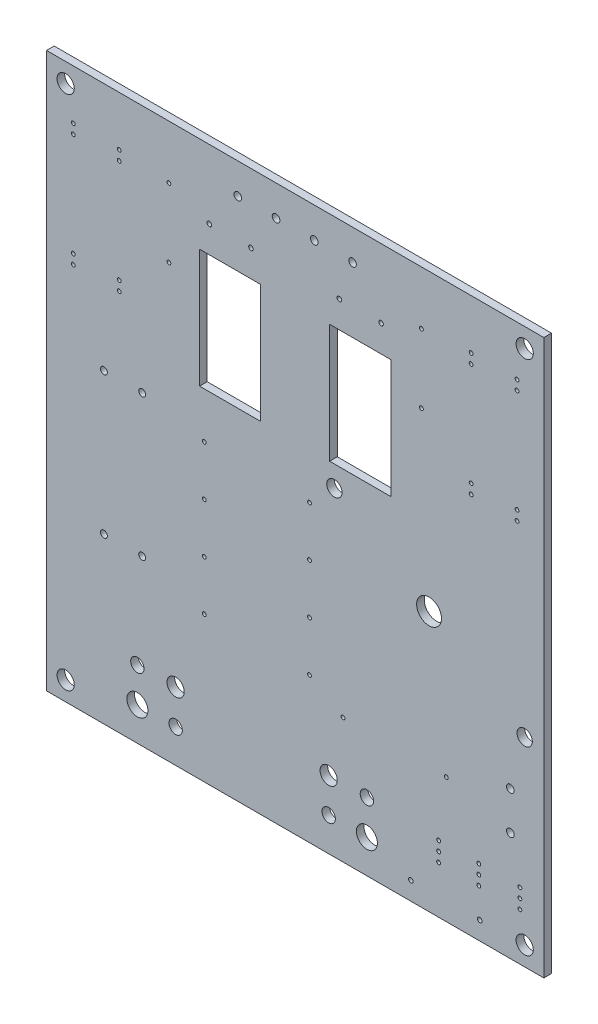
SolidWorks part; units mm, degrees
ref_plane "Спереди" through (0, 0, 0) normal (0, 0, 1) x (1, 0, 0)
ref_plane "Сверху" through (0, 0, 0) normal (0, 1, 0) x (1, 0, 0)
ref_plane "Справа" through (0, 0, 0) normal (1, 0, 0) x (0, 0, -1)
sketch "Эскиз1" plane through (0, 0, 0) normal (0, 0, 1) x (1, 0, 0)
  line L0 (-63.4221, 0) -> (70.5642, 0) construction
  line L1 (0, 51.5662) -> (0, -47.8522) construction
  line L2 (-56, 7.5) -> (-33, 7.5) construction
  line L3 (-65, -72.5) -> (65, -72.5)
  line L4 (-65, -72.5) -> (-65, 72.5)
  line L5 (-65, 72.5) -> (65, 72.5)
  line L6 (65, -72.5) -> (65, 72.5)
  circle A0 centre (-60, -67.5) radius 2.25
  circle A1 centre (60, -67.5) radius 2.25
  circle A2 centre (60, 67.5) radius 2.25
  circle A3 centre (-60, 67.5) radius 2.25
  circle A4 centre (35, -4.5) radius 3.25
  dimension "D3" = 4.5
  dimension "D6" = 6.5
  dimension "D1" = 130
  dimension "D2" = 145
  dimension "D4" = 5
  dimension "D5" = 5
  dimension "D7" = 100
  dimension "D8" = 68
  dimension "D11" = 80
extrude "Вытянуть1" add sketch "Эскиз1" along normal blind 2
sketch "Эскиз2" plane through (0, 0, 2) normal (0, 0, 1) x (1, 0, 0)
  line L0 (-65, -72.5) -> (65, -72.5) construction
  line L1 (-65, 72.5) -> (-65, -72.5) construction
  line L2 (37.5, -60.08) -> (72.5, -60.08) construction
  line L3 (37.5, -64.6595) -> (37.5, -83.93) construction
  line L4 (48, -64.5241) -> (48, -83.7946) construction
  line L5 (58.75, -64.5241) -> (58.75, -83.7946) construction
  line L6 (-29.4108, 64.5) -> (29.4956, 64.5) construction
  line L7 (60, -20.5) -> (48.4963, -20.5) construction
  line L8 (-65, 72.5) -> (-65, -72.5) construction
  line L9 (-65, 72.5) -> (-65, -72.5) construction
  line L10 (-65, -72.5) -> (65, -72.5) construction
  line L11 (-65, 72.5) -> (-65, -72.5) construction
  line L12 (-41.25, -54.75) -> (-41.25, -67.5) construction
  line L13 (18.75, -54.75) -> (18.75, -68.279) construction
  line L14 (-41.25, -63.75) -> (18.75, -63.75) construction
  line L15 (8.75, -63.75) -> (8.75, -54.75) construction
  line L16 (8.75, -54.75) -> (18.75, -54.75) construction
  circle A0 centre (-41.25, -54.75) radius 1.75
  circle A1 centre (18.75, -54.75) radius 1.75
  circle A4 centre (37.5, -55.08) radius 0.5
  circle A5 centre (37.5, -57.58) radius 0.5
  circle A6 centre (37.5, -60.08) radius 0.5
  circle A7 centre (48, -57.58) radius 0.5
  circle A8 centre (48, -60.08) radius 0.5
  circle A9 centre (48, -55.08) radius 0.5
  circle A10 centre (58.75, -55.08) radius 0.5
  circle A11 centre (58.75, -57.58) radius 0.5
  circle A12 centre (58.75, -60.08) radius 0.5
  circle A13 centre (-15, 64.5) radius 1
  circle A14 centre (-5, 64.5) radius 1
  circle A15 centre (5, 64.5) radius 1
  circle A16 centre (15, 64.5) radius 1
  circle A18 centre (60, -20.5) radius 2
  circle A19 centre (10.25, 11) radius 2
  circle A20 centre (-41.25, -63.75) radius 2.75
  circle A21 centre (18.75, -63.75) radius 2.75
  circle A22 centre (-31.25, -63.75) radius 1.75
  circle A23 centre (8.75, -63.75) radius 1.75
  circle A24 centre (8.75, -54.75) radius 2.25
  circle A25 centre (-31.25, -54.75) radius 2.25
  dimension "D4" = 83.75
  dimension "D5" = 3.5
  dimension "D10" = 1
  dimension "D11" = 12.42
  dimension "D12" = 5
  dimension "D13" = 2.5
  dimension "D15" = 2.5
  dimension "D17" = 2.5
  dimension "D18" = 1
  dimension "D19" = 2
  dimension "D21" = 10
  dimension "D22" = 10
  dimension "D23" = 20
  dimension "D33" = 2.5
  dimension "D34" = 2.5
  dimension "D36" = 5.5
  dimension "D39" = 5.5
  dimension "D40" = 10
  dimension "D41" = 10
  dimension "D42" = 4.5
  dimension "D43" = 10
  dimension "D44" = 9
  dimension "D46" = 4
  dimension "D25" = 4
  dimension "D1" = 17.75
  dimension "D3" = 23.75
  dimension "D14" = 113
  dimension "D16" = 123.75
  dimension "D20" = 137
  dimension "D24" = 50
  dimension "D28" = 52
  dimension "D29" = 75.25
  dimension "D30" = 125
  dimension "D31" = 102.5
  dimension "D32" = 12.42
  dimension "D35" = 17.75
  dimension "D37" = 8.75
  dimension "D38" = 8.75
  dimension "D45" = 83.5
extrude "Вырез-Вытянуть1" cut sketch "Эскиз2" against normal blind 2
sketch "Эскиз3" plane through (0, 0, 2) normal (0, 0, 1) x (1, 0, 0)
  line L0 (-17, 52.5) -> (17, 52.5) construction
  line L1 (-65, -72.5) -> (65, -72.5) construction
  line L2 (-65, 72.5) -> (-65, -72.5) construction
  line L3 (-30.9219, 54.5) -> (30.7658, 54.5) construction
  line L4 (17, 74.457) -> (17, 31.2292) construction
  line L5 (25, 16.5) -> (9, 16.5)
  line L6 (25, 16.5) -> (25, 47.5)
  line L7 (25, 47.5) -> (9, 47.5)
  line L8 (9, 16.5) -> (9, 47.5)
  line L9 (-17, 72.5) -> (-17, 24.5637) construction
  line L10 (65, 72.5) -> (-65, 72.5) construction
  line L11 (-65, -72.5) -> (65, -72.5) construction
  line L12 (56.25, -44) -> (56.25, -36.3329) construction
  line L13 (-65, 72.5) -> (-65, -72.5) construction
  line L14 (-65, -72.5) -> (65, -72.5) construction
  line L16 (-9, 16.5) -> (-25, 16.5)
  line L17 (-9, 16.5) -> (-9, 47.5)
  line L18 (-9, 47.5) -> (-25, 47.5)
  line L19 (-25, 16.5) -> (-25, 47.5)
  circle A0 centre (56.25, -34) radius 1
  circle A2 centre (-22.45, 54.5) radius 0.6
  circle A3 centre (-11.55, 54.5) radius 0.6
  circle A4 centre (11.55, 54.5) radius 0.6
  circle A5 centre (22.45, 54.5) radius 0.6
  circle A6 centre (56.25, -44) radius 1
  dimension "D6" = 10.9
  dimension "D7" = 10.9
  dimension "D10" = 1.2
  dimension "D5" = 74
  dimension "D8" = 127
  dimension "D18" = 10
  dimension "D19" = 2
  dimension "D2" = 16
  dimension "D3" = 31
  dimension "D4" = 120
  dimension "D9" = 16
  dimension "D13" = 121.25
  dimension "D14" = 28.5
  dimension "D16" = 31
  dimension "D17" = 40
extrude "Вырез-Вытянуть2" cut sketch "Эскиз3" against normal blind 2
sketch "Эскиз4" plane through (0, 0, 2) normal (0, 0, 1) x (1, 0, 0)
  line L0 (-65, -72.5) -> (65, -72.5) construction
  line L1 (-50, 7.5) -> (-40, 7.5) construction
  line L2 (-50, -29.5) -> (-40, -29.5) construction
  line L3 (-65, 72.5) -> (-65, -72.5) construction
  line L4 (-21.6791, -21.5) -> (11.4658, -21.5) construction
  line L5 (-22.7145, -34.5) -> (10.4304, -34.5) construction
  line L6 (-21.6791, -8.5) -> (11.4658, -8.5) construction
  line L7 (-21.6791, 4.5) -> (11.4658, 4.5) construction
  line L8 (27.5355, -67.75) -> (60.6804, -67.75) construction
  line L9 (-23.75, -34.5) -> (-23.75, -6.0227) construction
  line L10 (-65, 72.5) -> (-65, -72.5) construction
  line L11 (-65, -72.5) -> (65, -72.5) construction
  line L12 (33, 49.1621) -> (33, 15.9262) construction
  line L13 (-33, 46.4865) -> (-33, 18.7885) construction
  line L14 (-65, -72.5) -> (65, -72.5) construction
  circle A0 centre (-50, 7.5) radius 0.9
  circle A1 centre (-40, 7.5) radius 0.9
  circle A2 centre (-40, -29.5) radius 0.9
  circle A3 centre (-50, -29.5) radius 0.9
  circle A4 centre (-23.75, -21.5) radius 0.5
  circle A5 centre (3.75, -21.5) radius 0.5
  circle A6 centre (-23.75, -34.5) radius 0.5
  circle A7 centre (3.75, -34.5) radius 0.5
  circle A8 centre (-23.75, -8.5) radius 0.5
  circle A9 centre (3.75, -8.5) radius 0.5
  circle A10 centre (-23.75, 4.5) radius 0.5
  circle A11 centre (3.75, 4.5) radius 0.5
  circle A12 centre (30.25, -67.75) radius 0.6
  circle A13 centre (48.25, -67.75) radius 0.6
  circle A14 centre (33, 40.5) radius 0.5
  circle A15 centre (33, 58.5) radius 0.5
  circle A16 centre (-33, 40.5) radius 0.5
  circle A17 centre (-33, 58.5) radius 0.5
  dimension "D3" = 10
  dimension "D4" = 43
  dimension "D7" = 1.8
  dimension "D9" = 38
  dimension "D11" = 10
  dimension "D17" = 27.5
  dimension "D18" = 13
  dimension "D19" = 1
  dimension "D20" = 18
  dimension "D12" = 27.5
  dimension "D13" = 27.5
  dimension "D14" = 27.5
  dimension "D25" = 18
  dimension "D27" = 1
  dimension "D28" = 18
  dimension "D5" = 80
  dimension "D6" = 15
  dimension "D8" = 15
  dimension "D10" = 41.25
  dimension "D15" = 13
  dimension "D16" = 26
  dimension "D21" = 95.25
  dimension "D22" = 4.75
  dimension "D23" = 32
  dimension "D24" = 98
  dimension "D26" = 113
  dimension "D29" = 113
extrude "Вырез-Вытянуть3" cut sketch "Эскиз4" against normal blind 2
sketch "Эскиз5" plane through (0, 0, 2) normal (0, 0, 1) x (1, 0, 0)
  line L0 (-58, 30) -> (-58, 56.8053) construction
  line L1 (-65, 72.5) -> (-65, -72.5) construction
  line L2 (-65, -72.5) -> (65, -72.5) construction
  line L3 (-58, 30) -> (-37.7421, 30) construction
  line L4 (-46, 30) -> (-46, 56.7059) construction
  line L5 (65, -72.5) -> (65, 72.5) construction
  line L6 (46, 30) -> (46, 66.8053) construction
  line L7 (46, 30) -> (61.2579, 30) construction
  line L8 (58, 30) -> (58, 66.2925) construction
  line L9 (58, 30) -> (73.2579, 30) construction
  line L10 (12.1837, -39.75) -> (46, -39.75) construction
  line L11 (-65, 72.5) -> (-65, -72.5) construction
  circle A0 centre (-58, 30) radius 0.5
  circle A1 centre (-58, 57) radius 0.5
  circle A2 centre (-46, 30) radius 0.5
  circle A3 centre (-46, 57) radius 0.5
  circle A4 centre (46, 30) radius 0.5
  circle A5 centre (46, 57) radius 0.5
  circle A6 centre (58, 30) radius 0.5
  circle A7 centre (58, 57) radius 0.5
  circle A8 centre (-58, 27.5) radius 0.5
  circle A9 centre (-58, 59.5) radius 0.5
  circle A10 centre (-46, 59.5) radius 0.5
  circle A11 centre (-46, 27.5) radius 0.5
  circle A12 centre (46, 59.5) radius 0.5
  circle A13 centre (58, 59.5) radius 0.5
  circle A14 centre (46, 27.5) radius 0.5
  circle A15 centre (58, 27.5) radius 0.5
  circle A16 centre (12.5, -39.75) radius 0.5
  circle A17 centre (39.5, -39.75) radius 0.5
  dimension "D3" = 27
  dimension "D4" = 1
  dimension "D7" = 7
  dimension "D8" = 27
  dimension "D9" = 27
  dimension "D10" = 27
  dimension "D11" = 7
  dimension "D12" = 102.5
  dimension "D15" = 2.5
  dimension "D16" = 2.5
  dimension "D18" = 2.5
  dimension "D19" = 2.5
  dimension "D20" = 2.5
  dimension "D21" = 32.75
  dimension "D22" = 1
  dimension "D13" = 2.5
  dimension "D14" = 2.5
  dimension "D17" = 2.5
  dimension "D23" = 27
  dimension "D24" = 77.5
  dimension "D2" = 102.5
  dimension "D5" = 12
  dimension "D6" = 12
extrude "Вырез-Вытянуть4" cut sketch "Эскиз5" against normal blind 2
